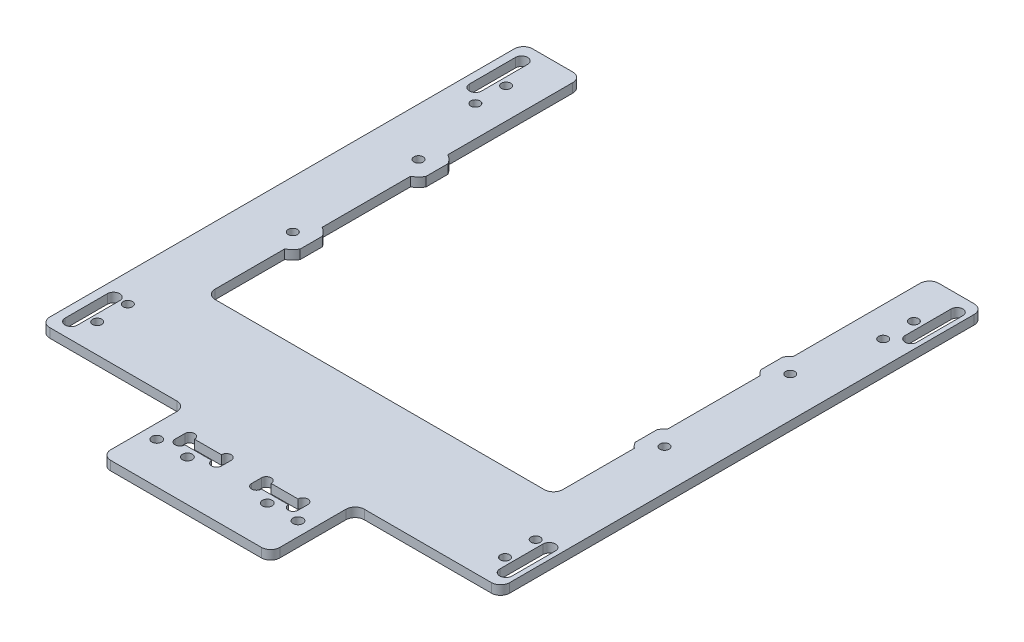
SolidWorks part; units mm, degrees
material "Thornel Mat VMA"
ref_plane "前视基准面" through (0, 0, 0) normal (0, 0, 1) x (1, 0, 0)
ref_plane "上视基准面" through (0, 0, 0) normal (0, 1, 0) x (1, 0, 0)
ref_plane "右视基准面" through (0, 0, 0) normal (1, 0, 0) x (0, 0, -1)
other "Configuration Table"
sketch "草图1" plane through (0, 0, 0) normal (0, 1, 0) x (1, 0, 0)
  line L0 (30.075, -69.59) -> (30.075, -66.41)
  line L1 (22.5, -69.59) -> (22.5, -66.41) construction
  line L7 (30.075, -68) -> (14.925, -68) construction
  line L8 (26.875, -69.59) -> (18.125, -69.59)
  line L9 (26.875, -66.41) -> (18.125, -66.41)
  line L14 (43.125, 69.59) -> (51.875, 69.59)
  line L15 (39.925, 69.59) -> (39.925, 66.41)
  line L16 (43.125, 66.41) -> (51.875, 66.41)
  line L17 (55.075, 69.59) -> (55.075, 66.41)
  line L18 (55.075, -69.59) -> (55.075, -66.41)
  line L19 (43.125, -66.41) -> (51.875, -66.41)
  line L20 (39.925, -69.59) -> (39.925, -66.41)
  line L21 (43.125, -69.59) -> (51.875, -69.59)
  line L22 (47.5, 69.59) -> (47.5, 66.41) construction
  line L23 (39.925, 68) -> (55.075, 68) construction
  line L24 (39.925, -68) -> (55.075, -68) construction
  line L25 (47.5, -69.59) -> (47.5, -66.41) construction
  line L27 (14.925, -69.59) -> (14.925, -66.41)
  line L29 (-1, -77.5) -> (-40, -77.5)
  line L30 (30.075, 68) -> (14.925, 68) construction
  line L31 (22.5, 69.59) -> (22.5, 66.41) construction
  line L33 (-1, 77.5) -> (-40, 77.5)
  line L54 (71, 77.5) -> (110, 77.5)
  line L56 (35, 153.4687) -> (35, -164.7089) construction
  line L58 (71, -77.5) -> (110, -77.5)
  line L64 (110, 235.15) -> (110, 77.5)
  line L67 (14.925, 69.59) -> (14.925, 66.41)
  line L68 (26.875, 66.41) -> (18.125, 66.41)
  line L69 (26.875, 69.59) -> (18.125, 69.59)
  line L70 (30.075, 69.59) -> (30.075, 66.41)
  line L72 (-40, 235.15) -> (110, 235.15)
  line L74 (-40, -235.15) -> (110, -235.15)
  line L77 (71, 77.5) -> (71, 47.9372)
  line L78 (-1, 77.5) -> (-1, 47.9372)
  line L84 (-40, 235.15) -> (-40, 77.5)
  line L85 (-1, 47.9372) -> (-43.8991, 47.9372)
  line L86 (-43.8991, 47.9372) -> (-43.8991, -47.9372)
  line L90 (113.8991, 47.9372) -> (113.8991, -47.9372)
  line L91 (71, 47.9372) -> (113.8991, 47.9372)
  line L93 (71, -47.9372) -> (113.8991, -47.9372)
  line L94 (-1, -47.9372) -> (-43.8991, -47.9372)
  line L95 (110, -77.5) -> (110, -235.15)
  line L96 (-1, -47.9372) -> (-1, -77.5)
  line L97 (71, -47.9372) -> (71, -77.5)
  line L98 (-40, -77.5) -> (-40, -235.15)
  arc A8 (39.925, 69.59) -> (43.125, 69.59) centre (41.525, 69.59) cw
  arc A9 (55.075, 69.59) -> (51.875, 69.59) centre (53.475, 69.59) ccw
  arc A10 (55.075, 66.41) -> (51.875, 66.41) centre (53.475, 66.41) cw
  arc A11 (39.925, 66.41) -> (43.125, 66.41) centre (41.525, 66.41) ccw
  arc A12 (39.925, -66.41) -> (43.125, -66.41) centre (41.525, -66.41) cw
  arc A13 (55.075, -66.41) -> (51.875, -66.41) centre (53.475, -66.41) ccw
  arc A14 (55.075, -69.59) -> (51.875, -69.59) centre (53.475, -69.59) cw
  arc A15 (39.925, -69.59) -> (43.125, -69.59) centre (41.525, -69.59) ccw
  circle A50 centre (48.025, -63.59) radius 1.6
  circle A51 centre (58.025, -63.59) radius 1.6
  circle A52 centre (58.025, 63.41) radius 1.6
  circle A53 centre (48.025, 63.41) radius 1.6
  arc A54 (30.075, -69.59) -> (26.875, -69.59) centre (28.475, -69.59) cw
  arc A55 (30.075, -66.41) -> (26.875, -66.41) centre (28.475, -66.41) ccw
  circle A56 centre (11.975, -63.59) radius 1.6
  circle A57 centre (21.975, -63.59) radius 1.6
  arc A58 (14.925, -69.59) -> (18.125, -69.59) centre (16.525, -69.59) ccw
  arc A59 (14.925, -66.41) -> (18.125, -66.41) centre (16.525, -66.41) cw
  circle A60 centre (21.975, 63.41) radius 1.6
  circle A61 centre (11.975, 63.41) radius 1.6
  arc A62 (30.075, 66.41) -> (26.875, 66.41) centre (28.475, 66.41) cw
  arc A63 (14.925, 66.41) -> (18.125, 66.41) centre (16.525, 66.41) ccw
  arc A64 (14.925, 69.59) -> (18.125, 69.59) centre (16.525, 69.59) cw
  arc A65 (30.075, 69.59) -> (26.875, 69.59) centre (28.475, 69.59) ccw
  point P28 (35, -97.5)
  point P79 (35, 97.5)
  point P141 (64, 0)
  point P146 (-64, 0)
  dimension "D12" = 4.925
extrude "凸台-拉伸1" add sketch "草图1" along normal blind 3
sketch "草图5" plane through (0, 0, 0) normal (0, -1, 0) x (1, 0, 0)
  line L0 (71, 77.5) -> (62.5724, 77.5)
  line L1 (62.5724, 77.5) -> (62.5724, 47.9372)
  line L2 (62.5724, 47.9372) -> (71, 47.9372)
  line L3 (71, 47.9372) -> (71, 77.5)
  line L4 (35, 235.15) -> (35, -235.15) construction
  line L5 (-40, 235.15) -> (110, 235.15) construction
  line L6 (110, -235.15) -> (-40, -235.15) construction
  line L7 (113.8991, 0) -> (-40.3263, 0) construction
  line L8 (113.8991, 47.9372) -> (113.8991, -47.9372) construction
  line L9 (7.4276, 47.9372) -> (-1, 47.9372)
  line L10 (7.4276, 77.5) -> (7.4276, 47.9372)
  line L11 (-1, 77.5) -> (7.4276, 77.5)
  line L12 (-1, 47.9372) -> (-1, 77.5)
  line L13 (7.4276, -77.5) -> (7.4276, -47.9372)
  line L14 (-1, -77.5) -> (7.4276, -77.5)
  line L15 (-1, -47.9372) -> (-1, -77.5)
  line L16 (7.4276, -47.9372) -> (-1, -47.9372)
  line L17 (62.5724, -47.9372) -> (71, -47.9372)
  line L18 (62.5724, -77.5) -> (62.5724, -47.9372)
  line L19 (71, -77.5) -> (62.5724, -77.5)
  line L20 (71, -47.9372) -> (71, -77.5)
  line L22 (64.9124, 72.165) -> (64.9124, 53.165) construction
  dimension "D1" = 2.34
extrude "切除-拉伸4" cut sketch "草图5" against normal blind 10
sketch "草图7" plane through (0, 0, 0) normal (0, -1, 0) x (-1, 0, 0)
  line L0 (-109.7412, -0.165) -> (39.4412, -0.165) construction
  line L1 (-109.7412, 46.835) -> (-109.7412, -47.165) construction
  line L2 (39.4412, -47.165) -> (39.4412, 46.835) construction
  line L3 (-113.8991, 0) -> (-113.8991, -47.9372)
  line L4 (-113.8991, -47.9372) -> (-113.8991, 47.9372) construction
  line L5 (-113.8991, -47.9372) -> (-62.5724, -47.9372)
  line L6 (-62.5724, -47.9372) -> (-62.5724, -50.2772)
  line L7 (-62.5724, -77.5) -> (-62.5724, -47.9372) construction
  line L8 (-62.5724, -50.2772) -> (-7.4276, -50.2772)
  line L9 (-7.4276, -47.9372) -> (-7.4276, -77.5) construction
  line L10 (-7.4276, -50.2772) -> (-7.4276, -47.9372)
  line L11 (-7.4276, -47.9372) -> (43.8991, -47.9372)
  line L12 (43.8991, -47.9372) -> (43.8991, 0)
  line L13 (43.8991, 47.9372) -> (43.8991, -47.9372) construction
  line L14 (43.8991, 47.6072) -> (43.8991, -0.33)
  line L15 (-7.4276, 47.6072) -> (43.8991, 47.6072)
  line L16 (-7.4276, 49.9472) -> (-7.4276, 47.6072)
  line L17 (-62.5724, 49.9472) -> (-7.4276, 49.9472)
  line L18 (-62.5724, 47.6072) -> (-62.5724, 49.9472)
  line L19 (-113.8991, 47.6072) -> (-62.5724, 47.6072)
  line L20 (-113.8991, -0.33) -> (-113.8991, 47.6072)
  dimension "D1" = 2.34
extrude "切除-拉伸-薄壁1" cut sketch "草图7" against normal blind 100 thin
sketch "草图8" plane through (0, 0, 0) normal (0, -1, 0) x (-1, 0, 0)
  line L0 (78.2129, 60.3854) -> (0, 54.3266)
  line L1 (0, 54.3266) -> (-4.4819, 51.6726)
  line L2 (-4.4819, 51.6726) -> (-7.9389, 48.7614)
  line L3 (-7.9389, 48.7614) -> (-49.3319, 46.578)
  line L4 (-49.3319, 46.578) -> (-63.5238, 48.7614)
  line L5 (-63.5238, 48.7614) -> (-79.0802, 55.8574)
  line L6 (-79.0802, 55.8574) -> (-126.5637, 60.3854)
  line L7 (-126.5637, 60.3854) -> (-136.5618, 25.02)
  line L8 (-136.5618, 25.02) -> (-185.5093, -177.4679)
  line L9 (-185.5093, -177.4679) -> (-114.7988, -331.7415)
  line L10 (-114.7988, -331.7415) -> (230.8962, -266.4277)
  line L11 (230.8962, -266.4277) -> (230.8962, -108.9334)
  line L12 (230.8962, -108.9334) -> (223.6813, -70.7462)
  line L13 (223.6813, -70.7462) -> (78.2129, 60.3854)
extrude "切除-拉伸5" cut sketch "草图8" against normal blind 100
sketch "草图9" plane through (0, 0, 0) normal (0, -1, 0) x (1, 0, 0)
  line L0 (-40, -102.5) -> (110, -102.5)
  line L1 (-40, -235.15) -> (-40, -77.5) construction
  line L2 (110, -77.5) -> (110, -235.15) construction
  line L3 (110, -102.5) -> (124.2117, -119.6913)
  line L4 (124.2117, -119.6913) -> (154.9872, -211.5735)
  line L5 (154.9872, -211.5735) -> (124.2117, -286.8618)
  line L6 (124.2117, -286.8618) -> (-63.6735, -270.7015)
  line L7 (-63.6735, -270.7015) -> (-75.5561, -182.7703)
  line L8 (-75.5561, -182.7703) -> (-74.082, -165.6324)
  line L9 (-74.082, -165.6324) -> (-40, -102.5)
  line L10 (-40, -77.5) -> (7.4276, -77.5) construction
  dimension "D1" = 25
extrude "切除-拉伸6" cut sketch "草图9" against normal blind 100
fillet "圆角3" radius 3 8 edges at (-40, 1.5, -102.5) (-40, 1.5, -77.5) (7.4276, 1.5, -77.5) (7.4276, 1.5, -49.9472) (62.5724, 1.5, -49.9472) (62.5724, 1.5, -77.5) (110, 1.5, -77.5) (110, 1.5, -102.5)
sketch "草图13" plane through (0, 3, 0) normal (0, 1, 0) x (1, 0, 0)
  line L0 (106.5254, 96.8471) -> (106.5254, 82.7172) construction
  line L1 (108.5254, 96.8471) -> (108.5254, 82.7172)
  line L2 (104.5254, 96.8471) -> (104.5254, 82.7172)
  line L3 (35, 102.5) -> (35, 49.9472) construction
  line L4 (-37, 102.5) -> (107, 102.5) construction
  line L5 (10.4276, 49.9472) -> (59.5724, 49.9472) construction
  line L6 (-35.2032, 96.4943) -> (-35.2032, 82.7172) construction
  line L9 (-33.2032, 96.4943) -> (-33.2032, 82.7172)
  line L10 (-37.2032, 96.4943) -> (-37.2032, 82.7172)
  arc A0 (108.5254, 96.8471) -> (104.5254, 96.8471) centre (106.5254, 96.8471) ccw
  arc A1 (104.5254, 82.7172) -> (108.5254, 82.7172) centre (106.5254, 82.7172) ccw
  arc A4 (-33.2032, 96.4943) -> (-37.2032, 96.4943) centre (-35.2032, 96.4943) ccw
  arc A5 (-37.2032, 82.7172) -> (-33.2032, 82.7172) centre (-35.2032, 82.7172) ccw
  point P2 (106.5254, 89.7822)
  point P15 (-36.3523, 89.7822)
  point P16 (-35.2032, 89.6058)
  dimension "D1" = 2
  dimension "D2" = 2
extrude "切除-拉伸10" cut sketch "草图13" against normal blind 10
sketch "草图14" plane through (0, 3, 0) normal (0, 1, 0) x (1, 0, 0)
  line L0 (110, 99.5) -> (110, 234.97)
  line L1 (110, 234.97) -> (-40, 234.97)
  line L2 (-40, 234.97) -> (-40, 99.5)
  line L3 (-37, 102.5) -> (107, 102.5) construction
  line L4 (-37, 102.5) -> (107, 102.5)
  arc A0 (110, 99.5) -> (107, 102.5) centre (107, 99.5) ccw construction
  arc A1 (-37, 102.5) -> (-40, 99.5) centre (-37, 99.5) ccw construction
  arc A2 (110, 99.5) -> (107, 102.5) centre (107, 99.5) ccw
  arc A3 (-37, 102.5) -> (-40, 99.5) centre (-37, 99.5) ccw
extrude "凸台-拉伸2" add sketch "草图14" against normal blind 3
fillet "圆角4" radius 3 2 edges at (110, 1.5, -234.97) (-40, 1.5, -234.97)
sketch "草图16" plane through (0, 3, 0) normal (0, 1, 0) x (1, 0, 0)
  line L0 (-35.3977, 229.7502) -> (-35.3977, 214.7502) construction
  line L4 (-36.8977, 229.7502) -> (-33.8977, 229.7502) construction
  line L7 (-33.8977, 214.7502) -> (-36.8977, 214.7502) construction
  line L8 (-33.4095, 229.7502) -> (-33.4095, 214.7502)
  line L9 (-37.3859, 229.7502) -> (-37.3859, 214.7502)
  line L10 (106.6032, 229.7502) -> (106.6032, 214.7502) construction
  line L11 (105.1032, 229.7502) -> (108.1032, 229.7502) construction
  line L12 (108.1032, 214.7502) -> (105.1032, 214.7502) construction
  line L13 (108.5134, 229.7502) -> (108.5134, 214.7502)
  line L14 (104.6929, 229.7502) -> (104.6929, 214.7502)
  arc A4 (-33.4095, 229.7502) -> (-37.3859, 229.7502) centre (-35.3977, 229.7502) ccw
  arc A5 (-37.3859, 214.7502) -> (-33.4095, 214.7502) centre (-35.3977, 214.7502) ccw
  arc A6 (108.5134, 229.7502) -> (104.6929, 229.7502) centre (106.6032, 229.7502) ccw
  arc A7 (104.6929, 214.7502) -> (108.5134, 214.7502) centre (106.6032, 214.7502) ccw
  point P4 (106.301, 221.9475)
  point P7 (-35.3977, 222.2502)
  point P9 (-34.2709, 222.8506)
  point P13 (106.6032, 222.2502)
extrude "切除-拉伸12" cut sketch "草图16" against normal blind 3
sketch "草图18" plane through (0, 3, 0) normal (0, 1, 0) x (1, 0, 0)
  circle A0 centre (102.1032, 96.8531) radius 1.5 construction
  circle A1 centre (102.1032, 86.8531) radius 1.5 construction
  circle A2 centre (102.1032, 96.8531) radius 1.5
  circle A3 centre (102.1032, 86.8531) radius 1.5
extrude "切除-拉伸13" cut sketch "草图18" against normal blind 10
sketch "草图19" plane through (0, 3, 0) normal (0, 1, 0) x (1, 0, 0)
  circle A0 centre (-30.8977, 86.8531) radius 1.5 construction
  circle A1 centre (-30.8977, 96.8531) radius 1.5 construction
  circle A2 centre (-30.8977, 86.8531) radius 1.5
  circle A3 centre (-30.8977, 96.8531) radius 1.5
extrude "切除-拉伸14" cut sketch "草图19" against normal blind 10
sketch "草图22" plane through (0, 0, 0) normal (0, -1, 0) x (1, 0, 0)
  line L4 (88.9335, -210.8856) -> (-17.4665, -210.8856)
  line L7 (88.9335, -210.8856) -> (88.9335, -118.3856)
  line L8 (-17.4665, -210.8856) -> (-17.4665, -118.3856)
  line L9 (88.9335, -118.3856) -> (-17.4665, -118.3856)
  circle A4 centre (96.8374, -185.1356) radius 1.5
  circle A5 centre (96.8374, -144.1356) radius 1.5
  circle A6 centre (-24.3704, -185.1356) radius 1.5
  circle A7 centre (-24.3704, -144.1356) radius 1.5
extrude "切除-拉伸15" cut sketch "草图22" against normal blind 10
sketch "草图23" plane through (0, 3, 0) normal (0, 1, 0) x (1, 0, 0)
  line L0 (-20.9265, 216.7175) -> (-20.9265, 112.3856)
  line L1 (-20.9265, 112.3856) -> (92.3935, 112.3856)
  line L2 (92.3935, 112.3856) -> (92.3935, 240.7263)
  line L3 (92.3935, 240.7263) -> (-20.9265, 240.7263)
  line L4 (-20.9265, 240.7263) -> (-20.9265, 216.7175)
  line L5 (-17.4665, 210.8856) -> (-17.4665, 118.3856) construction
  line L6 (88.9335, 118.3856) -> (88.9335, 210.8856) construction
  line L7 (-17.4665, 118.3856) -> (88.9335, 118.3856) construction
  dimension "D1" = 3.46
  dimension "D2" = 3.46
  dimension "D3" = 6
extrude "切除-拉伸16" cut sketch "草图23" against normal blind 10
fillet "圆角5" radius 3 4 edges at (-20.9265, 1.5, -234.97) (-20.9265, 1.5, -112.3856) (92.3935, 1.5, -112.3856) (92.3935, 1.5, -234.97)
sketch "草图24" plane through (0, 3, 0) normal (0, 1, 0) x (1, 0, 0)
  line L0 (-20.9265, 191.2298) -> (-20.9265, 179.0413)
  line L1 (-20.9265, 231.97) -> (-20.9265, 115.3856) construction
  line L2 (-20.9265, 150.2298) -> (-20.9265, 138.0413)
  line L3 (92.3935, 190.5441) -> (92.3935, 179.7271)
  line L4 (92.3935, 115.3856) -> (92.3935, 231.97) construction
  line L5 (92.3935, 149.5441) -> (92.3935, 138.7271)
  arc A0 (-20.9265, 179.0413) -> (-20.9265, 191.2298) centre (-24.3704, 185.1356) ccw
  arc A1 (-20.9265, 138.0413) -> (-20.9265, 150.2298) centre (-24.3704, 144.1356) ccw
  arc A2 (92.3935, 190.5441) -> (92.3935, 179.7271) centre (96.8374, 185.1356) ccw
  arc A3 (92.3935, 149.5441) -> (92.3935, 138.7271) centre (96.8374, 144.1356) ccw
  dimension "D1" = 14
  dimension "D2" = 14
  dimension "D3" = 14
  dimension "D4" = 14
extrude "凸台-拉伸4" add sketch "草图24" against normal blind 3
sketch "草图25" plane through (0, 3, 0) normal (0, 1, 0) x (1, 0, 0)
  line L0 (-18.3704, 193.4735) -> (-18.3704, 130.7892)
  line L1 (-18.3704, 130.7892) -> (90.8374, 130.7892)
  line L2 (90.8374, 130.7892) -> (90.8374, 206.7463)
  line L3 (90.8374, 206.7463) -> (-18.3704, 206.7463)
  line L4 (-18.3704, 206.7463) -> (-18.3704, 193.4735)
  arc A0 (-20.9265, 179.0413) -> (-20.9265, 191.2298) centre (-24.3704, 185.1356) ccw construction
  arc A2 (92.3935, 190.5441) -> (92.3935, 179.7271) centre (96.8374, 185.1356) ccw construction
  point P8 (-17.3704, 185.1356)
  dimension "D1" = 1
  dimension "D2" = 75.957
  dimension "D3" = 6
extrude "切除-拉伸17" cut sketch "草图25" against normal blind 45
sketch "草图26" plane through (0, 3, 0) normal (0, 1, 0) x (1, 0, 0)
  circle A2 centre (102.1032, 210.193) radius 1.5
  circle A3 centre (102.1032, 220.193) radius 1.5
extrude "切除-拉伸18" cut sketch "草图26" against normal blind 45
sketch "草图28" plane through (0, 3, 0) normal (0, 1, 0) x (1, 0, 0)
  circle A2 centre (-30.8977, 210.193) radius 1.5
  circle A3 centre (-30.8977, 220.193) radius 1.5
extrude "切除-拉伸19" cut sketch "草图28" against normal blind 45
